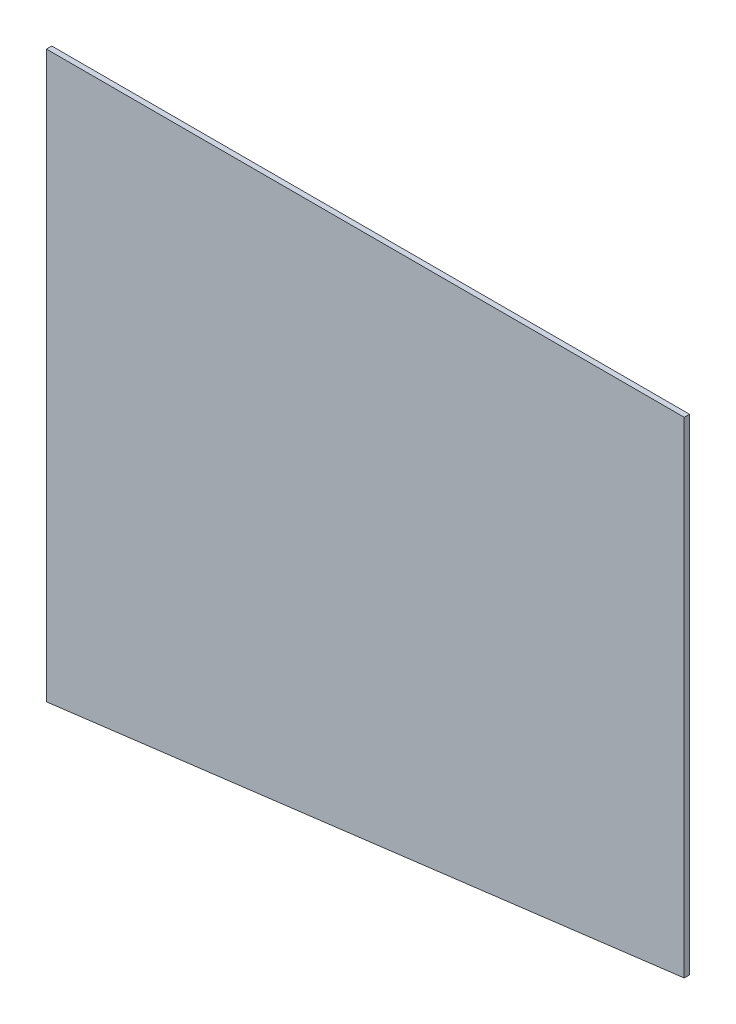
SolidWorks part; units mm, degrees
ref_plane "Front Plane" through (0, 0, 0) normal (0, 0, 1) x (1, 0, 0)
ref_plane "Top Plane" through (0, 0, 0) normal (0, 1, 0) x (1, 0, 0)
ref_plane "Right Plane" through (0, 0, 0) normal (1, 0, 0) x (0, 0, -1)
sketch "Sketch1" plane through (0, 0, 0) normal (0, 0, 1) x (1, 0, 0)
  line L0 (172.2857, -133.2344) -> (172.2857, 49.4916)
  line L1 (172.2857, 49.4916) -> (-67.7143, 49.4916)
  line L2 (-67.7143, 49.4916) -> (-67.7143, -163.2344)
  line L3 (-67.7143, -163.2344) -> (172.2857, -133.2344)
extrude "Boss-Extrude1" add sketch "Sketch1" along normal blind 2
